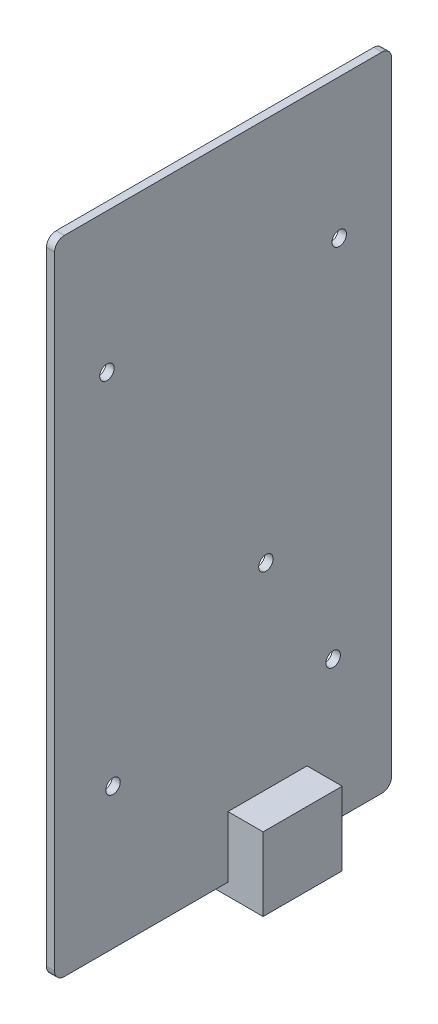
SolidWorks part; units mm, degrees
ref_plane "Front Plane" through (0, 0, 0) normal (0, 0, 1) x (1, 0, 0)
ref_plane "Top Plane" through (0, 0, 0) normal (0, 1, 0) x (1, 0, 0)
ref_plane "Right Plane" through (0, 0, 0) normal (1, 0, 0) x (0, 0, -1)
sketch "Sketch1" plane through (0, 0, 0) normal (1, 0, 0) x (0, 0, -1)
  line L1 (-33, 66.67) -> (33, 66.67)
  line L2 (-35, 64.67) -> (-35, -64.67)
  line L3 (-33, -66.67) -> (33, -66.67)
  line L4 (35, 64.67) -> (35, -64.67)
  circle A0 centre (-22.86, -37.46) radius 1.5
  circle A1 centre (22.86, -37.46) radius 1.5
  circle A2 centre (-24.13, 37.63) radius 1.5
  circle A3 centre (24.13, 37.63) radius 1.5
  arc A4 (-33, -66.67) -> (-35, -64.67) centre (-33, -64.67) cw
  arc A5 (35, -64.67) -> (33, -66.67) centre (33, -64.67) cw
  arc A6 (35, 64.67) -> (33, 66.67) centre (33, 64.67) ccw
  arc A7 (-33, 66.67) -> (-35, 64.67) centre (-33, 64.67) ccw
  circle A8 centre (8.89, -13.17) radius 1.5
  point P16 (-35, -66.67)
  point P19 (35, -66.67)
  point P22 (35, 66.67)
  dimension "D5" = 45.72
  dimension "D6" = 3
  dimension "D7" = 3
  dimension "D10" = 24.13
  dimension "D14" = 2
  dimension "D15" = 50.8
  dimension "D17" = 3
  dimension "D18" = 3
  dimension "D19" = 3
  dimension "D1" = 35
  dimension "D2" = 70
  dimension "D3" = 133.34
  dimension "D4" = 66.67
  dimension "D8" = 22.86
  dimension "D9" = 29.21
  dimension "D11" = 29.04
  dimension "D12" = 29.04
  dimension "D13" = 24.13
  dimension "D16" = 15.24
extrude "Boss-Extrude2" add sketch "Sketch1" along normal blind 1.7 contours A0 | A8 | A1 | A2 | A3 | L4 A5 L3 A4 L2 A7 L1 A6
sketch "Sketch2" plane through (1.7, 0, 0) normal (1, 0, 0) x (0, 0, -1)
  line L0 (35, 64.67) -> (35, -64.67) construction
  line L1 (1.01, -53.97) -> (17.44, -53.97)
  line L2 (1.01, -53.97) -> (1.01, -69.21)
  line L3 (1.01, -69.21) -> (17.44, -69.21)
  line L4 (17.44, -53.97) -> (17.44, -69.21)
  line L5 (-33, -66.67) -> (33, -66.67) construction
  dimension "D1" = 16.43
  dimension "D2" = 15.24
  dimension "D3" = 17.56
  dimension "D4" = 12.7
extrude "Boss-Extrude3" add sketch "Sketch2" along normal blind 7.3 and the other way blind 4.1 contours L3 L4 L1 L2
